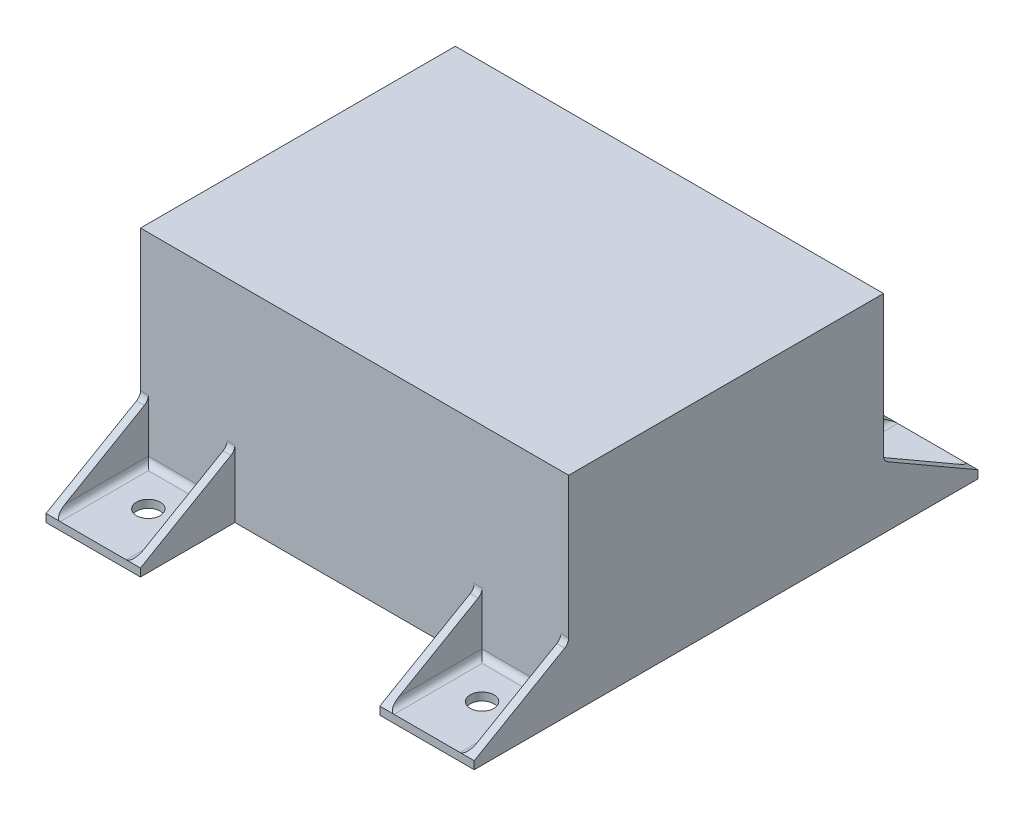
SolidWorks part; units mm, degrees
ref_plane "Front Plane" through (0, 0, 0) normal (0, 0, 1) x (1, 0, 0)
ref_plane "Top Plane" through (0, 0, 0) normal (0, 1, 0) x (1, 0, 0)
ref_plane "Right Plane" through (0, 0, 0) normal (1, 0, 0) x (0, 0, -1)
sketch "Sketch1" plane through (0, 0, 0) normal (0, 1, 0) x (1, 0, 0)
  line L1 (-86.36, -63.5) -> (86.36, -63.5)
  line L2 (-86.36, -63.5) -> (-86.36, 63.5)
  line L3 (-86.36, 63.5) -> (86.36, 63.5)
  line L4 (86.36, -63.5) -> (86.36, 63.5)
  line L5 (-86.36, -63.5) -> (86.36, 63.5) construction
  line L6 (-86.36, 63.5) -> (86.36, -63.5) construction
  point P0 (0, 0)
  dimension "D1" = 127
  dimension "D2" = 172.72
extrude "Boss-Extrude1" add sketch "Sketch1" along normal blind 83.82
shell "Shell1" thickness 3.175
sketch "Sketch6" plane through (0, 0, 0) normal (0, -1, 0) x (1, 0, 0)
  line L1 (-86.36, 63.5) -> (-48.26, 63.5)
  line L2 (-86.36, 63.5) -> (-86.36, 101.6)
  line L3 (-86.36, 101.6) -> (-48.26, 101.6)
  line L4 (-48.26, 63.5) -> (-48.26, 101.6)
  dimension "D1" = 38.1
  dimension "D2" = 38.1
extrude "Boss-Extrude4" add sketch "Sketch6" against normal blind 3.175
sketch "Sketch7" plane through (-86.36, 0, 0) normal (-1, 0, 0) x (0, 0, 1)
  line L0 (101.6, 3.175) -> (63.5, 25.172)
  line L1 (63.5, 83.82) -> (63.5, 3.175) construction
  line L2 (63.5, 25.172) -> (63.5, 3.175)
  line L3 (63.5, 3.175) -> (101.6, 3.175)
  dimension "D1" = 30
extrude "Boss-Extrude5" add sketch "Sketch7" against normal blind 3.175
ref_plane "Plane4" through (-67.31, 0, 0) normal (-1, 0, 0) x (0, 0, 1)
mirror "Mirror4" about plane through (-67.31, 0, 0) normal (-1, 0, 0) of "Boss-Extrude5"
mirror "Mirror5" about plane through (0, 0, 0) normal (0, 0, 1) of "Boss-Extrude4", "Mirror4", "Boss-Extrude5"
mirror "Mirror6" about plane through (0, 0, 0) normal (1, 0, 0) of "Mirror5", "Boss-Extrude4", "Boss-Extrude5", "Mirror4"
fillet "Fillet3" radius 2.54 12 edges at (-83.185, 3.175, 82.55) (-51.435, 3.175, 82.55) (-67.31, 3.175, 63.5) (83.185, 3.175, -82.55) (67.31, 3.175, -63.5) (51.435, 3.175, -82.55) (-83.185, 3.175, -82.55) (-51.435, 3.175, -82.55) (-67.31, 3.175, -63.5) (83.185, 3.175, 82.55) (67.31, 3.175, 63.5) (51.435, 3.175, 82.55)
hole_wizard "3/8 (0.375) Diameter Hole1" positions "Sketch8" profile "Sketch9" hole size "3/8" standard "ANSI Inch" end condition up to next
sketch "Sketch8" plane through (0, 3.175, 0) normal (0, 1, 0) x (1, 0, 0)
  line L0 (-67.31, -79.375) -> (-67.31, -101.6) construction
  line L1 (-53.975, -101.6) -> (-80.645, -101.6) construction
  point P0 (-67.31, -79.375)
  dimension "D1" = 22.225
sketch "Sketch9" plane through (-67.31, 3.175, 79.375) normal (1, 0, 0) x (0, 0, 1)
  line L0 (0, 0) -> (0, 3.176)
  line L1 (0, 3.176) -> (4.7625, 3.176)
  line L2 (4.7625, 3.176) -> (4.7625, 0)
  line L5 (4.7625, 0) -> (0, 0)
  line L11 (0, -6.35) -> (0, 107.95) construction
  dimension "Thru Hole Dia." = 9.525
  dimension "Thru Hole Depth" = 3.176
mirror "Mirror7" about plane through (0, 0, 0) normal (0, 0, 1) of "3/8 (0.375) Diameter Hole1"
mirror "Mirror8" about plane through (0, 0, 0) normal (1, 0, 0) of "Mirror7", "3/8 (0.375) Diameter Hole1"
fillet "Fillet4" radius 3.175 8 edges at (84.7725, 25.172, 63.5) (49.8475, 25.172, 63.5) (-49.8475, 25.172, 63.5) (-84.7725, 25.172, 63.5) (-84.7725, 25.172, -63.5) (-49.8475, 25.172, -63.5) (84.7725, 25.172, -63.5) (49.8475, 25.172, -63.5)
